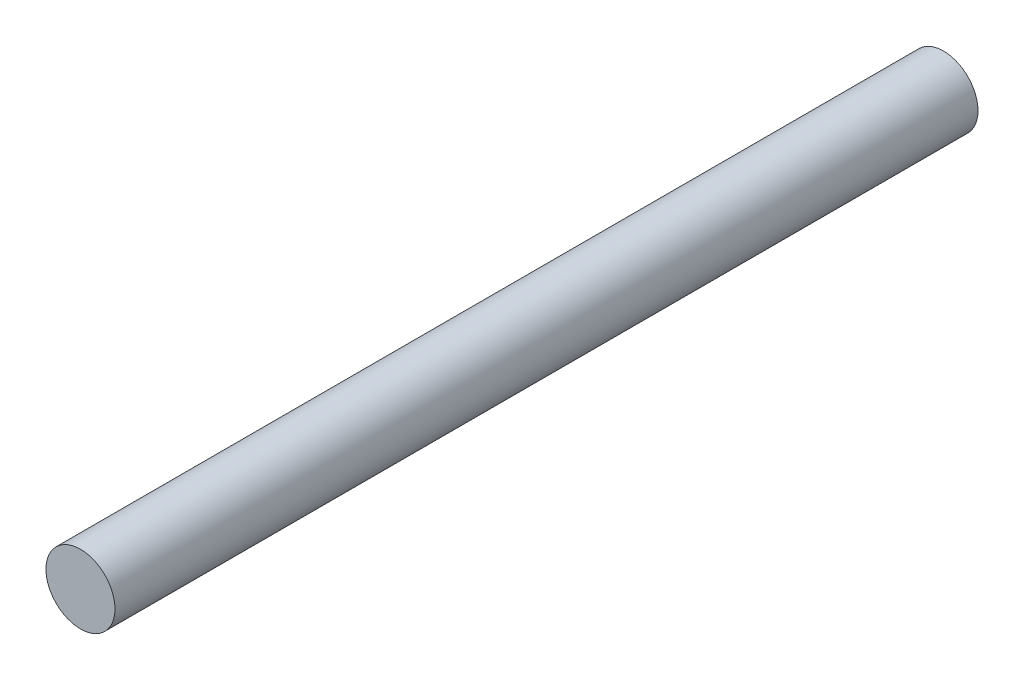
SolidWorks part; units mm, degrees
material "Alumina"
ref_plane "Front Plane" through (0, 0, 0) normal (0, 0, 1) x (1, 0, 0)
ref_plane "Top Plane" through (0, 0, 0) normal (0, 1, 0) x (1, 0, 0)
ref_plane "Right Plane" through (0, 0, 0) normal (1, 0, 0) x (0, 0, -1)
sketch "Sketch1" plane through (0, 0, 0) normal (0, 0, 1) x (1, 0, 0)
  circle A0 centre (0, 0) radius 4
  dimension "D1" = 8
extrude "Boss-Extrude1" add sketch "Sketch1" along normal blind 100 contours A0
